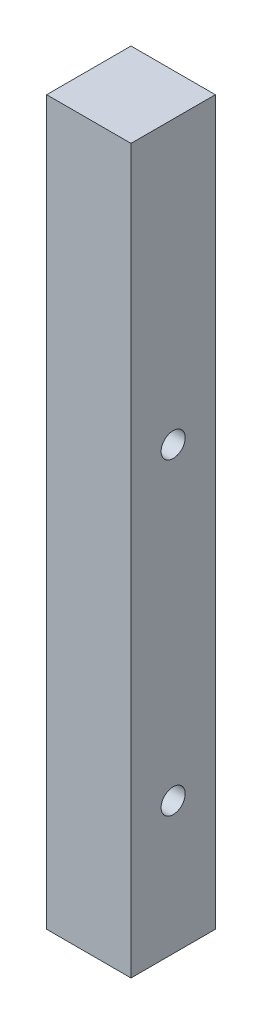
SolidWorks part; units mm, degrees
ref_plane "Front Plane" through (0, 0, 0) normal (0, 0, 1) x (1, 0, 0)
ref_plane "Top Plane" through (0, 0, 0) normal (0, 1, 0) x (1, 0, 0)
ref_plane "Right Plane" through (0, 0, 0) normal (1, 0, 0) x (0, 0, -1)
sketch "Sketch1" plane through (0, 0, 0) normal (0, 1, 0) x (1, 0, 0)
  line L1 (0, 0) -> (-70, 0)
  line L2 (0, 0) -> (0, -70)
  line L3 (0, -70) -> (-70, -70)
  line L4 (-70, 0) -> (-70, -70)
  dimension "D1" = 70
  dimension "D2" = 70
extrude "Boss-Extrude1" add sketch "Sketch1" along normal blind 600
sketch "Sketch2" plane through (0, 0, 0) normal (1, 0, 0) x (0, 0, -1)
  line L0 (-35, 0) -> (-35, 110)
  line L1 (-70, 0) -> (0, 0) construction
  line L2 (-35, 110) -> (-35, 366)
  circle A0 centre (-35, 110) radius 10
  circle A1 centre (-35, 366) radius 10
  point P7 (0, 0)
  dimension "D2" = 20
  dimension "D4" = 20
  dimension "D1" = 110
  dimension "D3" = 256
extrude "Cut-Extrude1" cut sketch "Sketch2" against normal blind 119 contours A0 | A1
